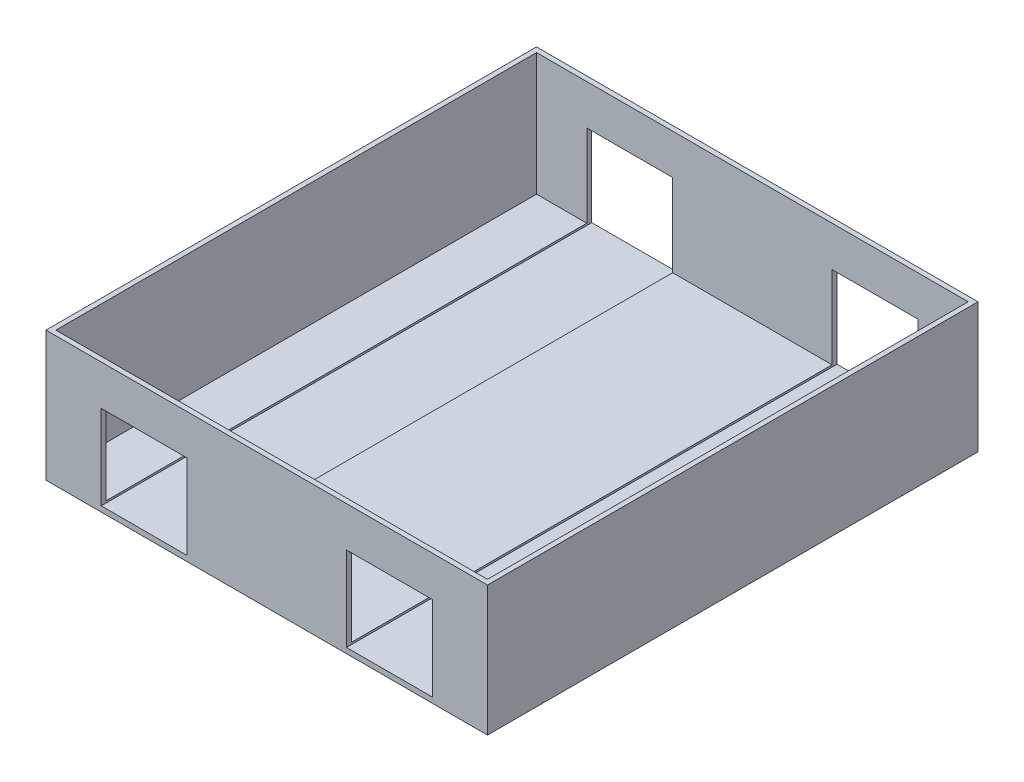
SolidWorks part; units mm, degrees
ref_plane "Front Plane" through (0, 0, 0) normal (0, 0, 1) x (1, 0, 0)
ref_plane "Top Plane" through (0, 0, 0) normal (0, 1, 0) x (1, 0, 0)
ref_plane "Right Plane" through (0, 0, 0) normal (1, 0, 0) x (0, 0, -1)
sketch "Sketch1" plane through (0, 0, 0) normal (0, 1, 0) x (1, 0, 0)
  line L1 (-90, 100) -> (90, 100)
  line L2 (-90, 100) -> (-90, -100)
  line L3 (-90, -100) -> (90, -100)
  line L4 (90, 100) -> (90, -100)
  line L5 (-90, 100) -> (90, -100) construction
  line L6 (-90, -100) -> (90, 100) construction
  point P0 (0, 0)
  dimension "D1" = 180
  dimension "D2" = 200
extrude "Boss-Extrude1" add sketch "Sketch1" along normal blind 3
sketch "Sketch2" plane through (0, 3, 0) normal (0, 1, 0) x (1, 0, 0)
  line L0 (-88, 98) -> (-88, -98)
  line L1 (-88, -98) -> (88, -98)
  line L2 (88, -98) -> (88, 98)
  line L3 (88, 98) -> (-88, 98)
  line L4 (90, -100) -> (90, 100)
  line L5 (90, 100) -> (-90, 100)
  line L6 (-90, 100) -> (-90, -100)
  line L7 (-90, -100) -> (90, -100)
  line L8 (90, -100) -> (90, 100)
  line L9 (90, 100) -> (-90, 100)
  line L10 (-90, 100) -> (-90, -100)
  line L11 (-90, -100) -> (90, -100)
  dimension "D1" = 0
  dimension "D2" = 2
extrude "Boss-Extrude2" add sketch "Sketch2" along normal blind 50
sketch "Sketch3" plane through (0, 0, 0) normal (0, 0, 1) x (1, 0, 0)
  line L0 (-90, 26.5) -> (90, 26.5) construction
  line L1 (-90, 53) -> (-90, 0) construction
  line L2 (90, 53) -> (90, 0) construction
  line L3 (0, 53) -> (0, 0) construction
  line L4 (-90, 53) -> (90, 53) construction
  line L5 (-50, 36.635) -> (-50, -11.9688) construction
  line L7 (-67.4925, 36.635) -> (-32.5075, 36.635)
  line L8 (-67.4925, 36.635) -> (-67.4925, 2.2)
  line L10 (-32.5075, 36.635) -> (-32.5075, 2.2)
  line L11 (-67.4925, 2.2) -> (-32.5075, 2.2)
  line L12 (50, 36.635) -> (50, -11.9688) construction
  line L13 (67.4925, 2.2) -> (32.5075, 2.2)
  line L14 (32.5075, 36.635) -> (32.5075, 2.2)
  line L15 (67.4925, 36.635) -> (67.4925, 2.2)
  line L16 (67.4925, 36.635) -> (32.5075, 36.635)
  line L17 (-90, 0) -> (90, 0) construction
  circle A0 centre (-50, 26.5) radius 40 construction
  circle A1 centre (50, 26.5) radius 40 construction
  dimension "D2" = 80
  dimension "D1" = 50
  dimension "D3" = 2.2
extrude "Cut-Extrude1" cut sketch "Sketch3" along normal through all both and the other way through all
